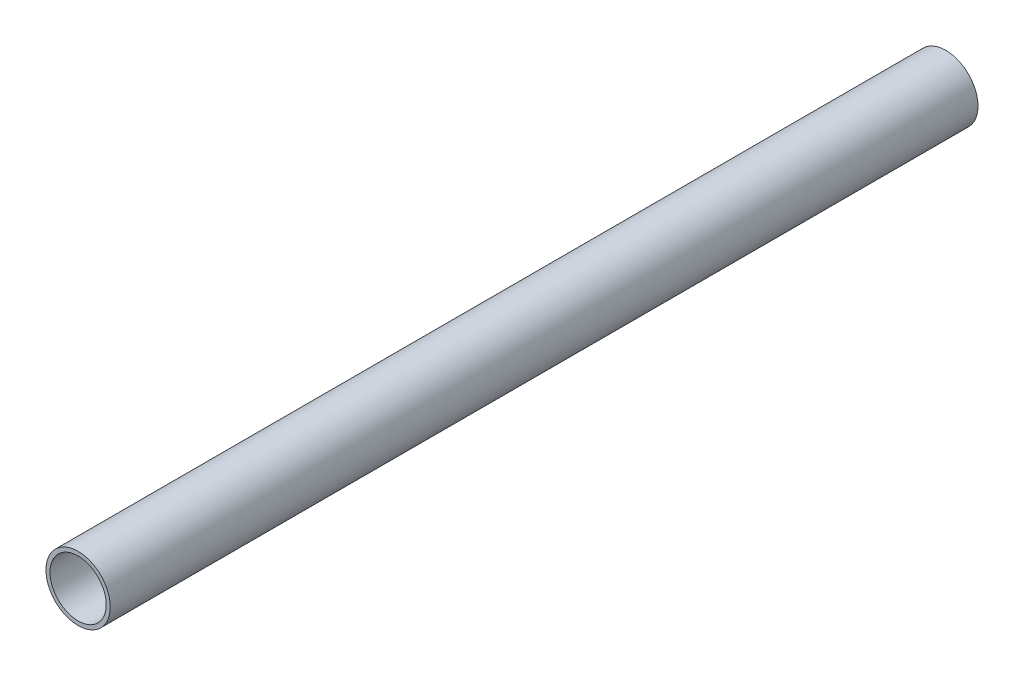
SolidWorks part; units mm, degrees
material "PC High Viscosity"
ref_plane "Front Plane" through (0, 0, 0) normal (0, 0, 1) x (1, 0, 0)
ref_plane "Top Plane" through (0, 0, 0) normal (0, 1, 0) x (1, 0, 0)
ref_plane "Right Plane" through (0, 0, 0) normal (1, 0, 0) x (0, 0, -1)
sketch "Sketch1" plane through (0, 0, 0) normal (0, 0, 1) x (1, 0, 0)
  circle A0 centre (0, 0) radius 12.7
  circle A1 centre (0, 0) radius 11.1125
  dimension "D1" = 25.4
  dimension "D2" = 1.5875
extrude "Boss-Extrude1" add sketch "Sketch1" along normal blind 342.62
